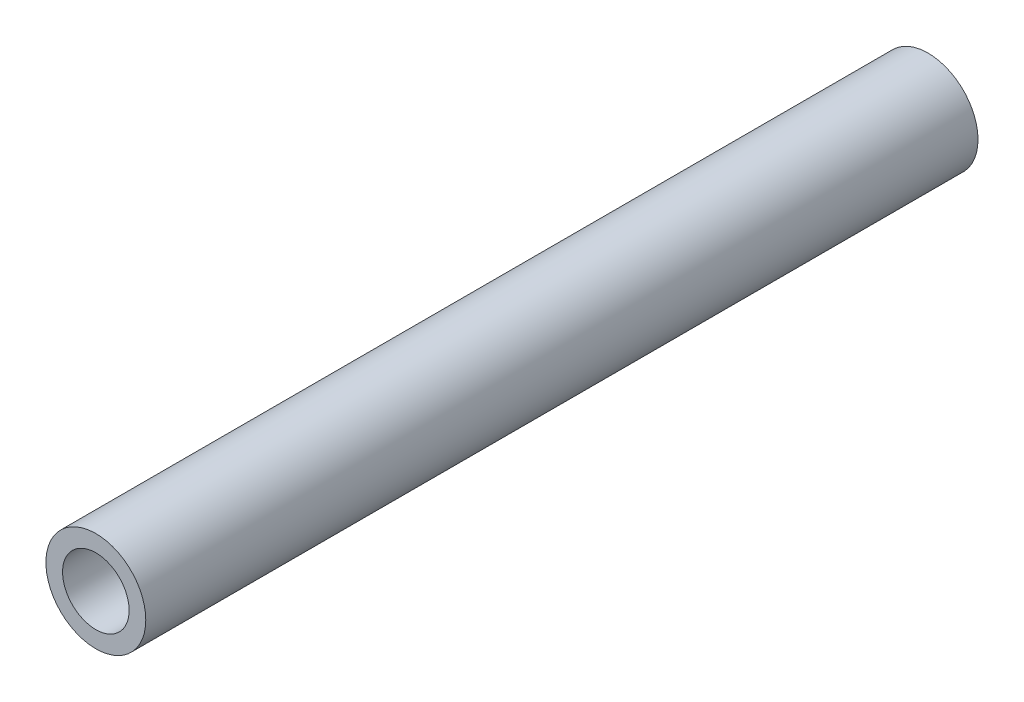
SolidWorks part; units mm, degrees
ref_plane "前视基准面" through (0, 0, 0) normal (0, 0, 1) x (1, 0, 0)
ref_plane "上视基准面" through (0, 0, 0) normal (0, 1, 0) x (1, 0, 0)
ref_plane "右视基准面" through (0, 0, 0) normal (1, 0, 0) x (0, 0, -1)
sketch "草图1" plane through (0, 0, 0) normal (0, 0, 1) x (1, 0, 0)
  circle A0 centre (0, 0) radius 3
  circle A1 centre (0, 0) radius 2
  dimension "D1" = 4
  dimension "D2" = 6
extrude "凸台-拉伸1" add sketch "草图1" along normal mid plane 50
